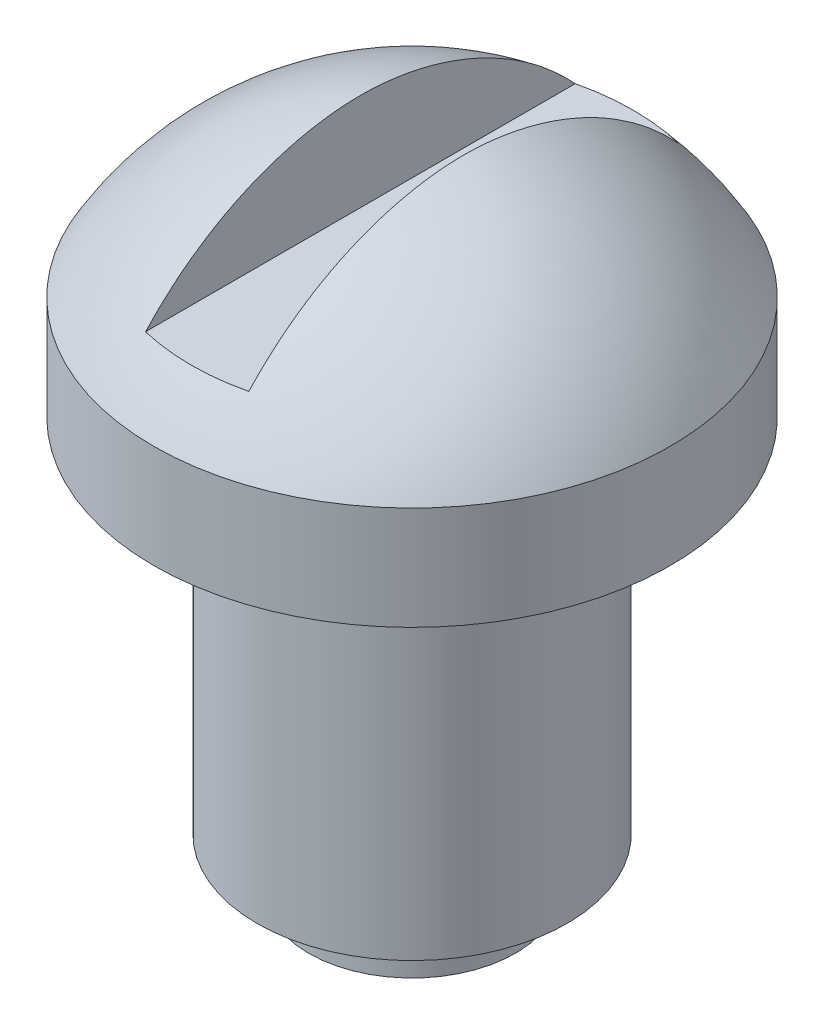
SolidWorks part; units mm, degrees
ref_plane "Front Plane" through (0, 0, 0) normal (0, 0, 1) x (1, 0, 0)
ref_plane "Top Plane" through (0, 0, 0) normal (0, 1, 0) x (1, 0, 0)
ref_plane "Right Plane" through (0, 0, 0) normal (1, 0, 0) x (0, 0, -1)
sketch "Sketch1" plane through (0, 0, 0) normal (0, 0, 1) x (1, 0, 0)
  line L0 (0, 49.9802) -> (0, -79.3803) construction
  line L1 (0, -64.4842) -> (2, -64.4842)
  line L2 (2, -64.4842) -> (2, -63.4842)
  line L3 (2, -63.4842) -> (3, -63.4842)
  line L4 (3, -63.4842) -> (3, -56.4842)
  line L5 (3, -56.4842) -> (5, -56.4842)
  line L6 (5, -56.4842) -> (5, -54.4842)
  line L7 (0, -51.4842) -> (0, -64.441)
  line L8 (0, -64.4842) -> (0, -64.441)
  arc A0 (5, -54.4842) -> (0, -51.4842) centre (-0.198, -57.4809) ccw
  point P5 (0, -51.4842)
  dimension "D6" = 3
  dimension "D7" = 6
  dimension "D1" = 2
  dimension "D2" = 1
  dimension "D3" = 7
  dimension "D4" = 2
  dimension "D5" = 2
revolve "Revolve2" add sketch "Sketch1" angle 360 about L0
sketch "Sketch2" plane through (0, 0, 0) normal (0, 0, 1) x (1, 0, 0)
  line L0 (5, -54.4842) -> (-5, -54.4842) construction
  line L1 (-1, -51.4842) -> (1, -51.4842)
  line L2 (-1, -51.4842) -> (-1, -53.4842)
  line L3 (-1, -53.4842) -> (1, -53.4842)
  line L4 (1, -51.4842) -> (1, -53.4842)
  dimension "D1" = 4
  dimension "D2" = 4
  dimension "D3" = 2
  dimension "D4" = 1
extrude "Cut-Extrude1" cut sketch "Sketch2" against normal through all and the other way through all
